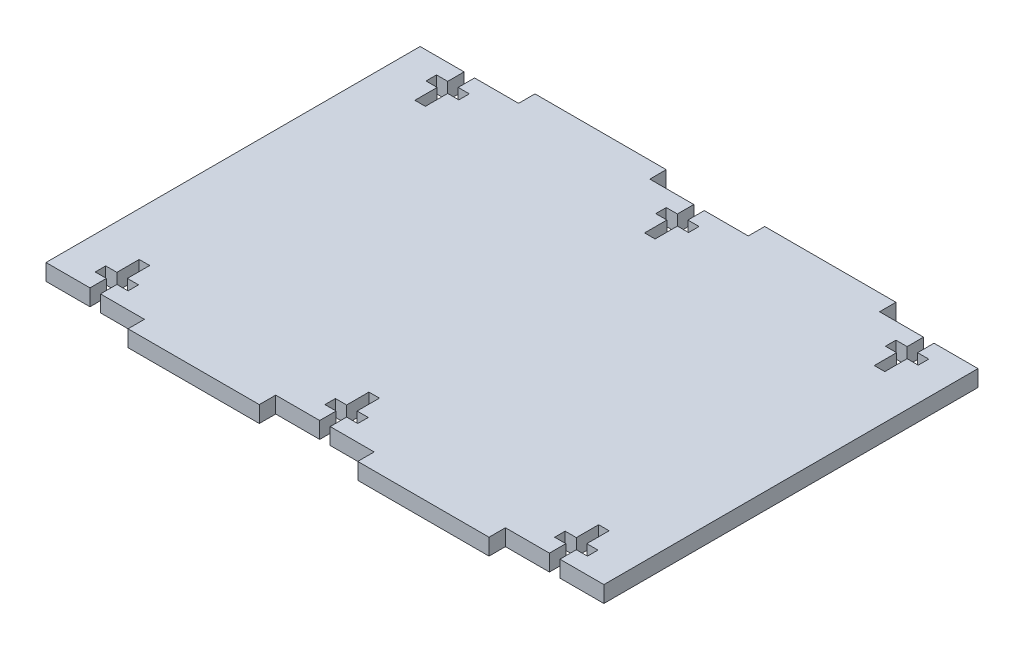
SolidWorks part; units mm, degrees
ref_plane "Front Plane" through (0, 0, 0) normal (0, 0, 1) x (1, 0, 0)
ref_plane "Top Plane" through (0, 0, 0) normal (0, 1, 0) x (1, 0, 0)
ref_plane "Right Plane" through (0, 0, 0) normal (1, 0, 0) x (0, 0, -1)
sketch "Sketch2" plane through (0, 0, 0) normal (0, 1, 0) x (1, 0, 0)
  line L2 (-107.95, -108.585) -> (-107.95, 36.195)
  line L3 (-107.95, 36.195) -> (-90.932, 36.195)
  line L4 (107.95, -108.585) -> (107.95, 36.195)
  line L5 (-107.95, -36.195) -> (107.95, 36.195) construction
  line L6 (-107.95, 36.195) -> (107.95, -36.195) construction
  line L8 (-69.85, 36.195) -> (-69.85, 42.545)
  line L10 (-19.05, 36.195) -> (-19.05, 42.545)
  line L12 (19.05, 36.195) -> (19.05, 42.545)
  line L14 (69.85, 36.195) -> (69.85, 42.545)
  line L16 (-69.85, 42.545) -> (-19.05, 42.545)
  line L17 (-90.932, 17.145) -> (-86.868, 17.145)
  line L18 (-90.932, 17.145) -> (-90.932, 25.781)
  line L20 (-86.868, 17.145) -> (-86.868, 25.781)
  line L25 (19.05, 42.545) -> (69.85, 42.545)
  line L27 (-95.25, 25.781) -> (-90.932, 25.781)
  line L28 (-95.25, 25.781) -> (-95.25, 29.845)
  line L29 (-95.25, 29.845) -> (-90.932, 29.845)
  line L30 (-82.55, 25.781) -> (-82.55, 29.845)
  line L36 (-86.868, 29.845) -> (-82.55, 29.845)
  line L37 (-86.868, 25.781) -> (-82.55, 25.781)
  line L42 (-101.6451, -36.195) -> (185.1976, -36.195) construction
  line L76 (-90.932, 29.845) -> (-90.932, 36.195)
  line L77 (-86.868, 29.845) -> (-86.868, 36.195)
  line L78 (-86.868, 36.195) -> (-69.85, 36.195)
  line L79 (-19.05, 36.195) -> (-2.032, 36.195)
  line L80 (-2.032, 17.145) -> (2.032, 17.145)
  line L81 (-2.032, 17.145) -> (-2.032, 25.781)
  line L82 (2.032, 17.145) -> (2.032, 25.781)
  line L83 (-6.35, 25.781) -> (-2.032, 25.781)
  line L84 (-6.35, 25.781) -> (-6.35, 29.845)
  line L85 (-6.35, 29.845) -> (-2.032, 29.845)
  line L86 (6.35, 25.781) -> (6.35, 29.845)
  line L87 (2.032, 29.845) -> (6.35, 29.845)
  line L88 (2.032, 25.781) -> (6.35, 25.781)
  line L89 (-2.032, 29.845) -> (-2.032, 36.195)
  line L90 (2.032, 29.845) -> (2.032, 36.195)
  line L91 (2.032, 36.195) -> (19.05, 36.195)
  line L92 (69.85, 36.195) -> (86.868, 36.195)
  line L93 (86.868, 17.145) -> (90.932, 17.145)
  line L94 (86.868, 17.145) -> (86.868, 25.781)
  line L95 (90.932, 17.145) -> (90.932, 25.781)
  line L96 (82.55, 25.781) -> (86.868, 25.781)
  line L97 (82.55, 25.781) -> (82.55, 29.845)
  line L98 (82.55, 29.845) -> (86.868, 29.845)
  line L99 (95.25, 25.781) -> (95.25, 29.845)
  line L100 (90.932, 29.845) -> (95.25, 29.845)
  line L101 (90.932, 25.781) -> (95.25, 25.781)
  line L102 (86.868, 29.845) -> (86.868, 36.195)
  line L103 (90.932, 29.845) -> (90.932, 36.195)
  line L104 (90.932, 36.195) -> (107.95, 36.195)
  line L105 (90.932, -108.585) -> (107.95, -108.585)
  line L106 (90.932, -102.235) -> (90.932, -108.585)
  line L107 (86.868, -102.235) -> (86.868, -108.585)
  line L108 (90.932, -98.171) -> (95.25, -98.171)
  line L109 (90.932, -102.235) -> (95.25, -102.235)
  line L110 (95.25, -98.171) -> (95.25, -102.235)
  line L111 (82.55, -102.235) -> (86.868, -102.235)
  line L112 (82.55, -98.171) -> (82.55, -102.235)
  line L113 (82.55, -98.171) -> (86.868, -98.171)
  line L114 (90.932, -89.535) -> (90.932, -98.171)
  line L115 (86.868, -89.535) -> (86.868, -98.171)
  line L116 (86.868, -89.535) -> (90.932, -89.535)
  line L117 (69.85, -108.585) -> (86.868, -108.585)
  line L118 (2.032, -108.585) -> (19.05, -108.585)
  line L119 (2.032, -102.235) -> (2.032, -108.585)
  line L120 (-2.032, -102.235) -> (-2.032, -108.585)
  line L121 (2.032, -98.171) -> (6.35, -98.171)
  line L122 (2.032, -102.235) -> (6.35, -102.235)
  line L123 (6.35, -98.171) -> (6.35, -102.235)
  line L124 (-6.35, -102.235) -> (-2.032, -102.235)
  line L125 (-6.35, -98.171) -> (-6.35, -102.235)
  line L126 (-6.35, -98.171) -> (-2.032, -98.171)
  line L127 (2.032, -89.535) -> (2.032, -98.171)
  line L128 (-2.032, -89.535) -> (-2.032, -98.171)
  line L129 (-2.032, -89.535) -> (2.032, -89.535)
  line L130 (-19.05, -108.585) -> (-2.032, -108.585)
  line L131 (-86.868, -108.585) -> (-69.85, -108.585)
  line L132 (-86.868, -102.235) -> (-86.868, -108.585)
  line L133 (-90.932, -102.235) -> (-90.932, -108.585)
  line L134 (-86.868, -98.171) -> (-82.55, -98.171)
  line L135 (-86.868, -102.235) -> (-82.55, -102.235)
  line L136 (-82.55, -98.171) -> (-82.55, -102.235)
  line L137 (-95.25, -102.235) -> (-90.932, -102.235)
  line L138 (-95.25, -98.171) -> (-95.25, -102.235)
  line L139 (-95.25, -98.171) -> (-90.932, -98.171)
  line L140 (19.05, -114.935) -> (69.85, -114.935)
  line L141 (-86.868, -89.535) -> (-86.868, -98.171)
  line L142 (-90.932, -89.535) -> (-90.932, -98.171)
  line L143 (-90.932, -89.535) -> (-86.868, -89.535)
  line L144 (-69.85, -114.935) -> (-19.05, -114.935)
  line L145 (69.85, -108.585) -> (69.85, -114.935)
  line L146 (19.05, -108.585) -> (19.05, -114.935)
  line L147 (-19.05, -108.585) -> (-19.05, -114.935)
  line L148 (-69.85, -108.585) -> (-69.85, -114.935)
  line L149 (-107.95, -108.585) -> (-90.932, -108.585)
  point P0 (0, 0)
  point P13 (18.3111, 36.195)
  point P17 (-35.0128, 36.195)
  point P74 (0, -72.39)
  point P78 (47.5824, 36.195)
  point P91 (107.4994, 36.0439)
  point P92 (48.5737, 36.195)
  point P93 (-34.2031, 36.195)
  dimension "D1" = 72.39
  dimension "D2" = 215.9
  dimension "D3" = 38.1
  dimension "D4" = 6.35
  dimension "D5" = 12.7
  dimension "D6" = 4.064
  dimension "D8" = 12.7
  dimension "D9" = 4.064
  dimension "D10" = 25.4
extrude "Boss-Extrude1" add sketch "Sketch2" along normal blind 6.35
